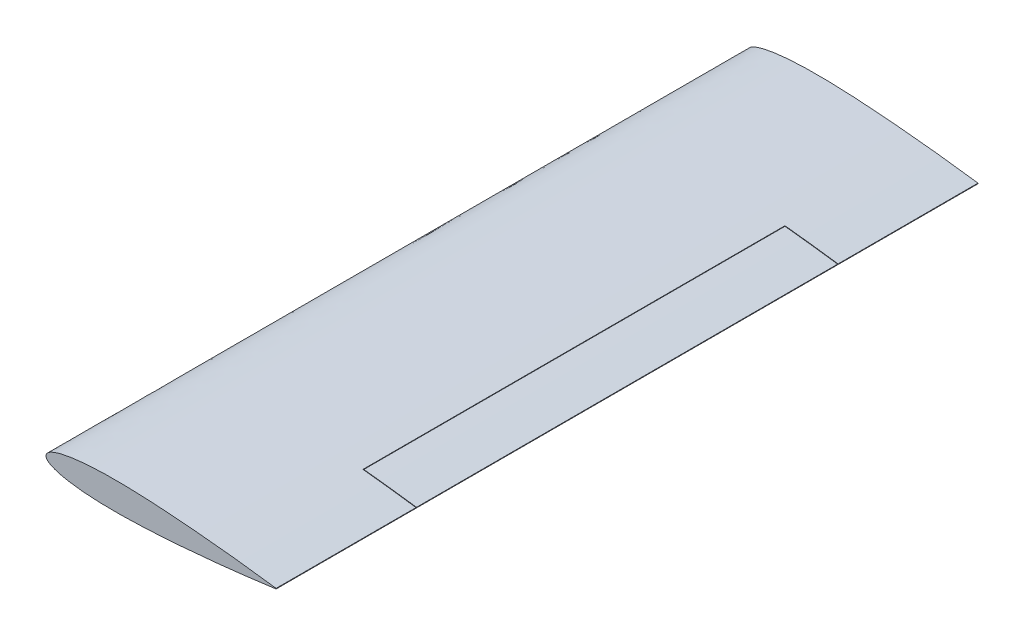
SolidWorks part; units mm, degrees
ref_plane "Front Plane" through (0, 0, 0) normal (0, 0, 1) x (1, 0, 0)
ref_plane "Top Plane" through (0, 0, 0) normal (0, 1, 0) x (1, 0, 0)
ref_plane "Right Plane" through (0, 0, 0) normal (1, 0, 0) x (0, 0, -1)
other "Center of Mass"
curve "Curve1"
  spline degree 3 poles (0, 0, 0) (0.003, 0.0365, 0) (0.009, 0.1114, 0) (0.0578, 0.22, 0) (0.134, 0.3245, 0) (0.2397, 0.4254, 0) (0.3736, 0.523, 0) (0.536, 0.6174, 0) (0.7264, 0.7086, 0) (0.9445, 0.7962, 0) (1.1898, 0.8801, 0) (1.462, 0.96, 0) (1.7603, 1.0355, 0) (2.0841, 1.1065, 0) (2.4327, 1.1725, 0) (2.8052, 1.2334, 0) (3.2008, 1.2888, 0) (3.6185, 1.3388, 0) (4.0575, 1.3829, 0) (4.5166, 1.4212, 0) (4.9948, 1.4535, 0) (5.491, 1.4798, 0) (6.0041, 1.5001, 0) (6.5327, 1.5144, 0) (7.0758, 1.5227, 0) (7.632, 1.5254, 0) (8.2001, 1.5224, 0) (8.7786, 1.514, 0) (9.3663, 1.5004, 0) (9.9618, 1.4819, 0) (10.5636, 1.4587, 0) (11.1705, 1.4311, 0) (11.7809, 1.3995, 0) (12.3935, 1.3642, 0) (13.0067, 1.3254, 0) (13.6193, 1.2836, 0) (14.2297, 1.2391, 0) (14.8366, 1.1921, 0) (15.4384, 1.1431, 0) (16.0339, 1.0922, 0) (16.6216, 1.0399, 0) (17.2001, 0.9864, 0) (17.7681, 0.9321, 0) (18.3242, 0.8771, 0) (18.8673, 0.8219, 0) (19.3959, 0.7666, 0) (19.9089, 0.7116, 0) (20.405, 0.657, 0) (20.8832, 0.6033, 0) (21.3422, 0.5505, 0) (21.7811, 0.499, 0) (22.1987, 0.449, 0) (22.5942, 0.4008, 0) (22.9666, 0.3545, 0) (23.3149, 0.3106, 0) (23.6385, 0.2691, 0) (23.9366, 0.2304, 0) (24.2084, 0.1946, 0) (24.4533, 0.1619, 0) (24.6708, 0.1326, 0) (24.8603, 0.1068, 0) (25.0214, 0.0847, 0) (25.1537, 0.0664, 0) (25.257, 0.052, 0) (25.3309, 0.0417, 0) (25.3753, 0.0355, 0) (25.3951, 0.0327, 0) (25.4, 0.032, 0) knots 0 0 0 0 0.004218 0.008652 0.013562 0.019137 0.0255 0.032726 0.040862 0.04993 0.05994 0.070892 0.082777 0.095581 0.109286 0.123868 0.139301 0.155557 0.172602 0.190404 0.208924 0.228125 0.247965 0.268401 0.289388 0.310881 0.332832 0.35519 0.377906 0.400928 0.424203 0.447679 0.471299 0.49501 0.518757 0.542484 0.566136 0.589657 0.612992 0.636087 0.658886 0.681338 0.703388 0.724985 0.746079 0.766619 0.786556 0.805845 0.82444 0.842296 0.859372 0.875627 0.891023 0.905523 0.919093 0.9317 0.943314 0.953909 0.963457 0.971937 0.979328 0.985613 0.990775 0.994804 0.997688 0.999422 1 1 1 1
curve "Curve2"
  spline degree 3 poles (0.0148, -0.1082, 0) (0.028, -0.1443, 0) (0.0559, -0.2205, 0) (0.1346, -0.3244, 0) (0.2395, -0.4254, 0) (0.3737, -0.523, 0) (0.536, -0.6174, 0) (0.7264, -0.7086, 0) (0.9445, -0.7962, 0) (1.1898, -0.8801, 0) (1.462, -0.96, 0) (1.7603, -1.0355, 0) (2.0841, -1.1065, 0) (2.4327, -1.1725, 0) (2.8052, -1.2334, 0) (3.2008, -1.2888, 0) (3.6185, -1.3388, 0) (4.0575, -1.3829, 0) (4.5166, -1.4212, 0) (4.9948, -1.4535, 0) (5.491, -1.4798, 0) (6.0041, -1.5001, 0) (6.5327, -1.5144, 0) (7.0758, -1.5227, 0) (7.632, -1.5254, 0) (8.2001, -1.5224, 0) (8.7786, -1.514, 0) (9.3663, -1.5004, 0) (9.9618, -1.4819, 0) (10.5636, -1.4587, 0) (11.1705, -1.4311, 0) (11.7809, -1.3995, 0) (12.3935, -1.3642, 0) (13.0067, -1.3254, 0) (13.6193, -1.2836, 0) (14.2297, -1.2391, 0) (14.8366, -1.1921, 0) (15.4384, -1.1431, 0) (16.0339, -1.0922, 0) (16.6216, -1.0399, 0) (17.2001, -0.9864, 0) (17.7681, -0.9321, 0) (18.3242, -0.8771, 0) (18.8673, -0.8219, 0) (19.3959, -0.7666, 0) (19.9089, -0.7116, 0) (20.405, -0.657, 0) (20.8832, -0.6033, 0) (21.3422, -0.5505, 0) (21.7811, -0.499, 0) (22.1987, -0.449, 0) (22.5942, -0.4008, 0) (22.9666, -0.3545, 0) (23.3149, -0.3106, 0) (23.6385, -0.2691, 0) (23.9366, -0.2304, 0) (24.2084, -0.1946, 0) (24.4533, -0.1619, 0) (24.6708, -0.1326, 0) (24.8603, -0.1068, 0) (25.0214, -0.0847, 0) (25.1537, -0.0664, 0) (25.257, -0.052, 0) (25.3309, -0.0417, 0) (25.3753, -0.0355, 0) (25.3951, -0.0327, 0) (25.4, -0.032, 0) knots 0 0 0 0 0.004453 0.009384 0.014983 0.021372 0.028629 0.036799 0.045906 0.055959 0.066957 0.078892 0.091751 0.105513 0.120157 0.135656 0.15198 0.169098 0.186975 0.205574 0.224856 0.24478 0.265302 0.286379 0.307962 0.330006 0.352459 0.375271 0.398391 0.421765 0.445339 0.46906 0.492871 0.516719 0.540546 0.564298 0.587919 0.611353 0.634545 0.657442 0.679988 0.702132 0.723821 0.745003 0.76563 0.785652 0.805023 0.823696 0.841628 0.858776 0.8751 0.890561 0.905123 0.91875 0.93141 0.943074 0.953713 0.963302 0.971818 0.979241 0.985552 0.990736 0.994782 0.997678 0.999419 1 1 1 1
sketch "Sketch1" plane through (0, 0, 0) normal (0, 0, 1) x (1, 0, 0)
  line L0 (0, 0) -> (0.0742, -0.5411)
  line L1 (127, 0.16) -> (127, -0.16)
  spline S2 degree 3 poles (0.0742, -0.5411) (0.1402, -0.7217) (0.2794, -1.1023) (0.673, -1.6219) (1.1974, -2.1272) (1.8685, -2.615) (2.6798, -3.0872) (3.6318, -3.5429) (4.7223, -3.9812) (5.9492, -4.4007) (7.31, -4.8) (8.8016, -5.1777) (10.4206, -5.5323) (12.1634, -5.8624) (14.0259, -6.1668) (16.0039, -6.4442) (18.0926, -6.6938) (20.2874, -6.9146) (22.583, -7.106) (24.9741, -7.2675) (27.4552, -7.3989) (30.0204, -7.5003) (32.6637, -7.5718) (35.3791, -7.6137) (38.1601, -7.6269) (41.0003, -7.6119) (43.8929, -7.5699) (46.8314, -7.5019) (49.8088, -7.4093) (52.8181, -7.2933) (55.8524, -7.1556) (58.9045, -6.9976) (62.9897, -6.7619) (67.0743, -6.4928) (72.1532, -6.1221) (77.1616, -5.7236) (82.1152, -5.2913) (86.9285, -4.8463) (91.5567, -4.3963) (96.0742, -3.9303) (100.3424, -3.4723) (104.3213, -3.0299) (108.8003, -2.5098) (112.8562, -2.0199) (115.9539, -1.6325) (118.1927, -1.3456) (120.4545, -1.0515) (122.9821, -0.715) (125.1839, -0.4131) (126.3836, -0.2463) (126.7779, -0.1912) (127, -0.16) knots 0 0 0 0 0.004453 0.009384 0.014983 0.021372 0.028629 0.036799 0.045906 0.055959 0.066957 0.078892 0.091751 0.105513 0.120157 0.135656 0.15198 0.169098 0.186975 0.205574 0.224856 0.24478 0.265302 0.286379 0.307962 0.330006 0.352459 0.375271 0.398391 0.421765 0.445339 0.46906 0.492871 0.540546 0.564298 0.611353 0.657442 0.679988 0.723821 0.76563 0.785652 0.823696 0.858776 0.890561 0.91875 0.93141 0.943074 0.971818 0.990736 0.994782 1 1 1 1
  spline S3 degree 3 poles (0, 0) (0.0148, 0.1826) (0.0451, 0.5571) (0.2892, 1.1001) (0.6698, 1.6226) (1.1984, 2.127) (1.8682, 2.615) (2.6799, 3.0872) (3.6318, 3.5429) (4.7223, 3.9812) (5.9492, 4.4007) (7.31, 4.8) (8.8016, 5.1777) (10.4206, 5.5323) (12.1634, 5.8624) (14.0259, 6.1668) (16.0039, 6.4442) (18.0926, 6.6938) (20.2874, 6.9146) (22.583, 7.106) (24.9741, 7.2675) (27.4552, 7.3989) (30.0204, 7.5003) (32.6637, 7.5718) (35.3791, 7.6137) (38.1601, 7.6269) (41.0003, 7.6119) (43.8929, 7.5699) (46.8314, 7.5019) (49.8088, 7.4093) (52.8181, 7.2933) (55.8524, 7.1556) (58.9045, 6.9976) (62.9897, 6.7619) (67.0743, 6.4928) (72.1532, 6.1221) (77.1616, 5.7236) (82.1152, 5.2913) (86.9285, 4.8463) (91.5567, 4.3963) (96.0742, 3.9303) (100.3424, 3.4723) (104.3213, 3.0299) (108.8003, 2.5098) (112.8562, 2.0199) (115.9539, 1.6325) (118.1927, 1.3456) (120.4545, 1.0515) (122.9821, 0.715) (125.1839, 0.4131) (126.3836, 0.2463) (126.7779, 0.1912) (127, 0.16) knots 0 0 0 0 0.004218 0.008652 0.013562 0.019137 0.0255 0.032726 0.040862 0.04993 0.05994 0.070892 0.082777 0.095581 0.109286 0.123868 0.139301 0.155557 0.172602 0.190404 0.208924 0.228125 0.247965 0.268401 0.289388 0.310881 0.332832 0.35519 0.377906 0.400928 0.424203 0.447679 0.471299 0.49501 0.542484 0.566136 0.612992 0.658886 0.681338 0.724985 0.766619 0.786556 0.82444 0.859372 0.891023 0.919093 0.9317 0.943314 0.971937 0.990775 0.994804 1 1 1 1
  point P0 (127, 0)
  dimension "D1" = 127
extrude "Boss-Extrude1" add sketch "Sketch1" along normal blind 387.35
sketch "Sketch2" plane through (0, 0, 0) normal (0, 1, 0) x (1, 0, 0)
  line L0 (0, 0) -> (0, -193.675) construction
  line L1 (0, -387.35) -> (0, 0) construction
  line L2 (0, -193.675) -> (127, -193.675) construction
  line L3 (127, -387.35) -> (127, 0) construction
  line L5 (114.3, -206.375) -> (12.7, -206.375)
  line L6 (114.3, -206.375) -> (114.3, -180.975)
  line L7 (114.3, -180.975) -> (12.7, -180.975)
  line L8 (12.7, -206.375) -> (12.7, -180.975)
  line L9 (114.3, -206.375) -> (12.7, -180.975) construction
  line L10 (114.3, -180.975) -> (12.7, -206.375) construction
  point P5 (63.5, -193.675)
  point P14 (63.5, -193.675)
  point P17 (63.5, -193.675)
  dimension "D1" = 101.6
  dimension "D2" = 25.4
hole_wizard "1/4 (0.25) Diameter Hole1" positions "Sketch2" profile "Sketch4" hole size "1/4" standard "ANSI Inch"
sketch "Sketch4" plane through (76.2, 0, 254) normal (1, 0, 0) x (0, 0, -1)
  line L0 (0, 0) -> (0, 9.1522)
  line L1 (0, 9.1522) -> (3.175, 9.1522)
  line L2 (3.175, 9.1522) -> (3.175, 0)
  line L5 (3.175, 0) -> (0, 0)
  line L11 (0, -6.35) -> (0, 107.95) construction
  dimension "Thru Hole Dia." = 6.35
  dimension "Thru Hole Depth" = 9.1522
ref_plane "Plane1" through (0, 25.4, 0) normal (0, 1, 0) x (1, 0, 0)
sketch "Sketch5" plane through (0, 25.4, 0) normal (0, 1, 0) x (1, 0, 0)
  line L4 (12.7, -206.375) -> (114.3, -206.375)
  line L5 (12.7, -180.975) -> (12.7, -206.375)
  line L6 (114.3, -180.975) -> (12.7, -180.975)
  line L7 (114.3, -206.375) -> (114.3, -180.975)
  line L8 (12.7, -206.375) -> (114.3, -206.375)
  line L9 (12.7, -180.975) -> (12.7, -206.375)
  line L10 (114.3, -180.975) -> (12.7, -180.975)
  line L11 (114.3, -206.375) -> (114.3, -180.975)
  dimension "D1" = 0
hole_wizard "1/4 (0.25) Diameter Hole3" positions "Sketch5" profile "Sketch7" hole size "1/4" standard "ANSI Inch"
sketch "Sketch7" plane through (127, 25.4, 266.7) normal (1, 0, 0) x (0, 0, 1)
  line L0 (0, 0) -> (0, 34.5522)
  line L1 (0, 34.5522) -> (3.175, 34.5522)
  line L2 (3.175, 34.5522) -> (3.175, 0)
  line L5 (3.175, 0) -> (0, 0)
  line L11 (0, -6.35) -> (0, 107.95) construction
  dimension "Thru Hole Dia." = 6.35
  dimension "Thru Hole Depth" = 34.5522
sketch "Sketch8" plane through (0, 0, 0) normal (0, 1, 0) x (1, 0, 0)
  line L0 (127, 0) -> (127, -77.47) construction
  line L1 (156.0513, -309.88) -> (97.9488, -309.88)
  line L2 (156.0513, -309.88) -> (156.0513, -77.47)
  line L3 (156.0513, -77.47) -> (97.9488, -77.47)
  line L4 (97.9488, -309.88) -> (97.9488, -77.47)
  dimension "D1" = 77.47
  dimension "D2" = 232.41
  dimension "D3" = 58.1025
extrude "Cut-Extrude-Thin1" cut sketch "Sketch8" against normal blind 25.4 and the other way blind 25.4 thin thin type one direction wall 0.254
equation "\"span\"= 48"
equation "\"wing_chord\"= 9"
equation "\"fuse_len\"= 15"
equation "\"fuse_height\"= 5"
equation "\"fuse_wid\"= 5"
equation "\"foam_t\"= 0.1875"
equation "\"main_spar_len\"= 36"
equation "\"x_fuse_to_wing\"= 3"
equation "\"x_cg_from_le\"= 2.25"
equation "\"boom_len\"= 30"
equation "\"wing_angle\"= 1.5"
equation "\"boom_d\"= 0.75"
equation "\"wing_spar_d\"= 0.375"
equation "\"wing_spar_l\"= 48"
equation "\"wing_spar_spacing\"= 1.35"
equation "\"wing_mount_l\"= 2.5"
equation "\"vstab_span\"= 6.5"
equation "\"hstab_span\"= 15.25"
equation "\"tail_chord\"= 5"
equation "\"D1@Boss-Extrude1\"=\"hstab_span\""
equation "\"D1@Sketch8\"=\"hstab_span\"*0.2"
equation "\"D2@Sketch8\"=\"hstab_span\"*0.6"
equation "\"D3@Sketch8\"=\"hstab_span\"*0.15"
